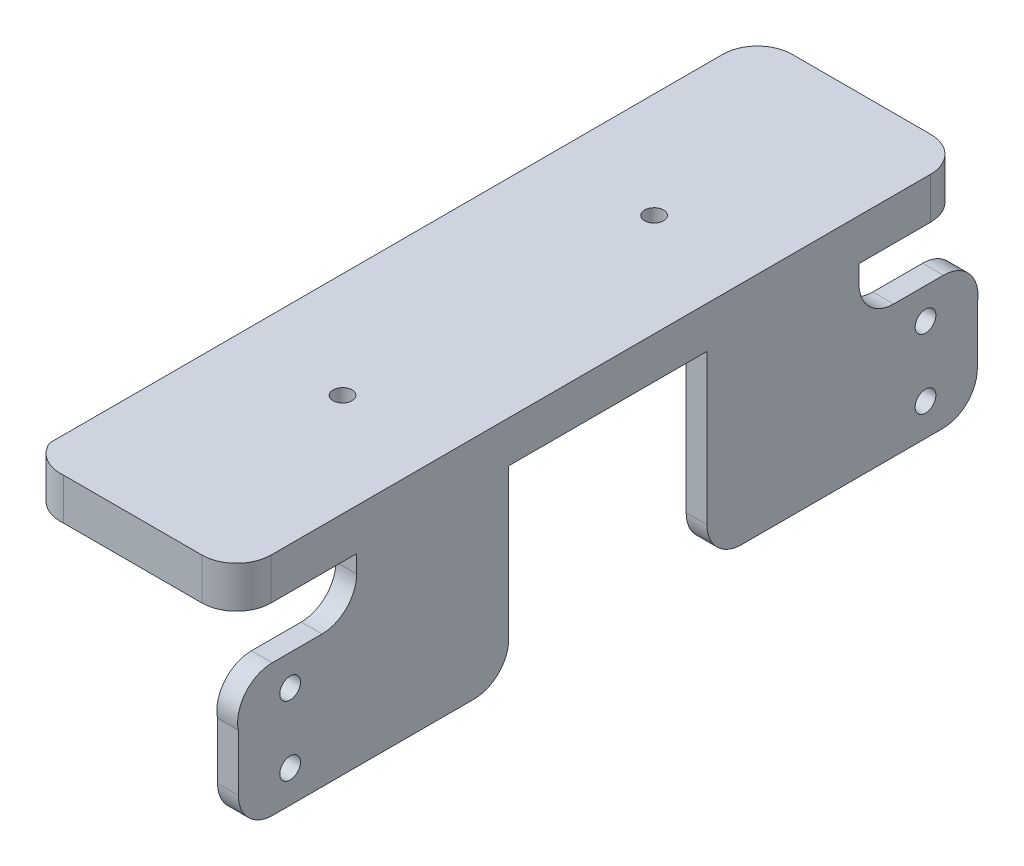
SolidWorks part; units mm, degrees
ref_plane "Front Plane" through (0, 0, 0) normal (0, 0, 1) x (1, 0, 0)
ref_plane "Top Plane" through (0, 0, 0) normal (0, 1, 0) x (1, 0, 0)
ref_plane "Right Plane" through (0, 0, 0) normal (1, 0, 0) x (0, 0, -1)
sketch "Sketch1" plane through (0, 0, 0) normal (0, 1, 0) x (1, 0, 0)
  line L1 (-10, 51.6038) -> (10, 51.6038)
  line L2 (-15, 46.6038) -> (-15, -50.6234)
  line L3 (-10, -53.6136) -> (10, -53.6136)
  line L4 (15, 46.6038) -> (15, -48.6136)
  line L5 (-15, 53.6136) -> (15, -53.6136) construction
  line L6 (-15, -53.6136) -> (15, 53.6136) construction
  line L18 (7.1034, -38.6136) -> (7.1034, 36.6038)
  line L19 (-6.7618, -1.0049) -> (-6.7618, -38.6136)
  line L20 (-6.7618, 36.6038) -> (-6.7618, -1.0049)
  arc A0 (-15, -50.6234) -> (-10, -53.6136) centre (-10.4142, -48.6308) ccw
  arc A1 (10, -53.6136) -> (15, -48.6136) centre (10, -48.6136) ccw
  arc A2 (10, 51.6038) -> (15, 46.6038) centre (10, 46.6038) cw
  arc A3 (-10, 51.6038) -> (-15, 46.6038) centre (-10, 46.6038) ccw
  circle A12 centre (0.1855, 21.4948) radius 1.364
  circle A14 centre (0.1855, -23.4894) radius 1.364
  spline S4 degree 3 poles (-6.7618, -38.6136) (-6.7618, -39.0364) (-6.6818, -39.9076) (-6.3104, -41.1995) (-5.6668, -42.442) (-4.7662, -43.5506) (-3.6576, -44.4512) (-2.4152, -45.0948) (-1.1231, -45.4663) (0.1708, -45.585) (1.4648, -45.4663) (2.7567, -45.0948) (3.9992, -44.4512) (5.1078, -43.5506) (6.0084, -42.442) (6.652, -41.1996) (7.0235, -39.9075) (7.1034, -39.0365) (7.1034, -38.6136) knots -37.859639 -37.859639 -37.859639 -37.859639 -35.654499 -33.316868 -30.881728 -28.394729 -25.90773 -23.47259 -21.134959 -18.929819 -16.724679 -14.387049 -11.951909 -9.46491 -6.97791 -4.54277 -2.20514 0 0 0 0
  spline S5 degree 3 poles (7.1034, 36.6038) (7.1034, 37.0266) (7.0235, 37.8978) (6.652, 39.1897) (6.0084, 40.4322) (5.1078, 41.5408) (3.9992, 42.4414) (2.7568, 43.085) (1.4647, 43.4565) (0.1708, 43.5752) (-1.1232, 43.4565) (-2.4151, 43.085) (-3.6576, 42.4414) (-4.7662, 41.5408) (-5.6668, 40.4322) (-6.3104, 39.1898) (-6.6819, 37.8977) (-6.7618, 37.0267) (-6.7618, 36.6038) knots -37.859639 -37.859639 -37.859639 -37.859639 -35.654499 -33.316868 -30.881728 -28.394729 -25.90773 -23.47259 -21.134959 -18.929819 -16.724679 -14.387049 -11.951909 -9.46491 -6.97791 -4.54277 -2.20514 0 0 0 0
  point P0 (0, 0)
  dimension "D4" = 5
  dimension "D7" = 0.1855
  dimension "D1" = 2.7281
  dimension "D2" = 2.7281
  dimension "D6" = 5
  dimension "D8" = 6.9179
  dimension "D5" = 20
  dimension "D9" = 6.7618
  dimension "D10" = 3.6524
  dimension "D13" = 15.109
  dimension "D14" = 15
  dimension "D16" = 22.4845
  dimension "D17" = 15.1242
extrude "Boss-Extrude1" add sketch "Sketch1" along normal blind 6 contours L18 S5 L20 L19 S4 A12 A14 | L1 A3 L2 A0 L3 A1 L4 A2 S5 L18 S4 L19 L20
sketch "Sketch3" plane through (15, 0, 0) normal (1, 0, 0) x (0, 0, -1)
  line L4 (36.2669, 6) -> (14.3086, 6)
  line L6 (36.2669, 6) -> (36.2669, -2.5521)
  line L7 (41.2669, -7.5521) -> (48.4492, -7.5521)
  line L18 (53.3481, -13.5521) -> (53.3481, -21.6714)
  line L19 (48.3481, -26.6714) -> (19.3086, -26.6714)
  line L22 (14.3086, 6) -> (14.3086, -21.6714)
  line L25 (46.6038, 0) -> (-48.6136, 0) construction
  line L34 (36.2669, 6) -> (14.3086, 6)
  arc A10 (48.4492, -7.5521) -> (53.3481, -13.5521) centre (48.4492, -12.5521) cw
  arc A11 (36.2669, -2.5521) -> (41.2669, -7.5521) centre (41.2669, -2.5521) ccw
  arc A12 (53.3481, -21.6714) -> (48.3481, -26.6714) centre (48.3481, -21.6714) cw
  arc A19 (19.3086, -26.6714) -> (14.3086, -21.6714) centre (19.3086, -21.6714) cw
  circle A70 centre (45.8685, -22.0022) radius 1.5
  circle A94 centre (45.8685, -12.0022) radius 1.5
  line M41 (-48.6136, 0) -> (46.6038, 0)
  dimension "D2" = 3
  dimension "D3" = 5
  dimension "D5" = 5
  dimension "D1" = 3
  dimension "D4" = 5
  dimension "D6" = 6.7443
  dimension "D7" = 1.8454
  dimension "D8" = 32.2952
  dimension "D9" = 0.7353
  dimension "D10" = 9.6016
  dimension "D11" = 6
  dimension "D12" = 26.6714
  dimension "D13" = 7.5521
  dimension "D14" = 4.4501
  dimension "D16" = 8.4501
sketch "Sketch4" plane through (15, 0, 0) normal (1, 0, 0) x (0, 0, -1)
  line L18 (0, 0) -> (0, -27.9299) construction
  line L28 (46.6038, 0) -> (-48.6136, 0) construction
  line L29 (-36.2669, 6) -> (-14.3086, 6)
  line L30 (-14.3086, 6) -> (-14.3086, -21.6714)
  line L31 (-48.3481, -26.6714) -> (-19.3086, -26.6714)
  line L32 (-53.3481, -13.5521) -> (-53.3481, -21.6714)
  line L33 (-41.2669, -7.5521) -> (-48.4492, -7.5521)
  line L34 (-36.2669, 6) -> (-36.2669, -2.5521)
  line L35 (-36.2669, 6) -> (-14.3086, 6)
  arc A24 (-14.3086, -21.6714) -> (-19.3086, -26.6714) centre (-19.3086, -21.6714) cw
  arc A25 (-48.3481, -26.6714) -> (-53.3481, -21.6714) centre (-48.3481, -21.6714) cw
  arc A26 (-53.3481, -13.5521) -> (-48.4492, -7.5521) centre (-48.4492, -12.5521) cw
  arc A27 (-36.2669, -2.5521) -> (-41.2669, -7.5521) centre (-41.2669, -2.5521) cw
  circle A28 centre (-45.8685, -12.0022) radius 1.5
  circle A29 centre (-45.8685, -22.0022) radius 1.5
  line M11 (-48.6136, 0) -> (46.6038, 0)
  dimension "D1" = 3
  dimension "D2" = 3
  dimension "D3" = 5
  dimension "D4" = 99.952
  dimension "D5" = 5
  dimension "D6" = 5
  dimension "D7" = 46.6038
  dimension "D8" = 14.3086
  dimension "D9" = 21.9583
  dimension "D10" = 9.6016
  dimension "D11" = 2.5807
  dimension "D12" = 6
  dimension "D13" = 26.6714
  dimension "D14" = 7.5521
  dimension "D15" = 4.4501
  dimension "D17" = 8.4501
extrude "Boss-Extrude5" add sketch "Sketch4" against normal blind 3 contours L34 A27 L33 A26 L32 A25 L31 A24 L30 A28 A29 M11
extrude "Boss-Extrude6" add sketch "Sketch3" against normal blind 3 contours A19 L19 A12 L18 A10 L7 A11 L6 L22 A94 A70 M41
